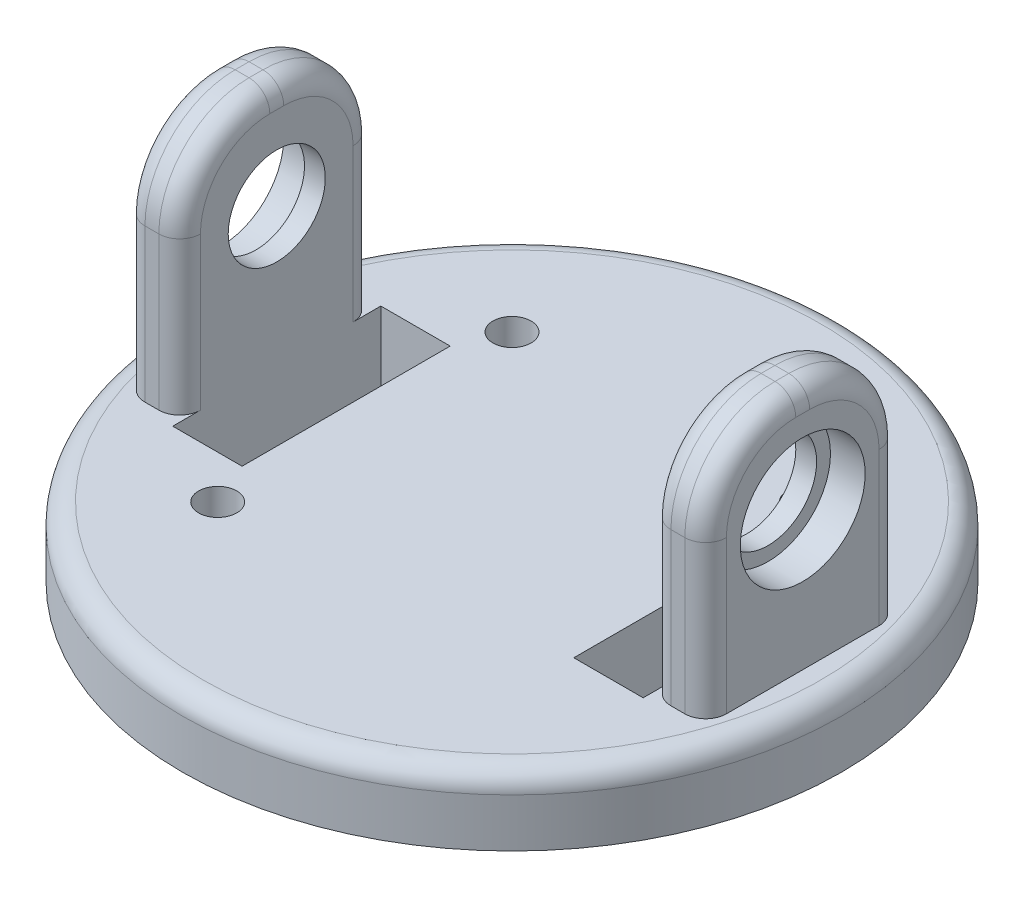
SolidWorks part; units mm, degrees
ref_plane "Front Plane" through (0, 0, 0) normal (0, 0, 1) x (1, 0, 0)
ref_plane "Top Plane" through (0, 0, 0) normal (0, 1, 0) x (1, 0, 0)
ref_plane "Right Plane" through (0, 0, 0) normal (1, 0, 0) x (0, 0, -1)
sketch "Sketch1" plane through (0, 0, 0) normal (0, 1, 0) x (1, 0, 0)
  circle A0 centre (0, 0) radius 47.5
  dimension "D1" = 95
extrude "Boss-Extrude1" add sketch "Sketch1" along normal blind 10
sketch "Sketch2" plane through (0, 10, 0) normal (0, 1, 0) x (1, 0, 0)
  line L0 (0, 0) -> (0, -17.7493) construction
  line L1 (-41.91, 14) -> (-33.91, 14)
  line L2 (-41.91, 14) -> (-41.91, -14)
  line L3 (-41.91, -14) -> (-33.91, -14)
  line L4 (-33.91, 14) -> (-33.91, -14)
  line L9 (33.91, 14) -> (33.91, -14)
  line L10 (41.91, -14) -> (33.91, -14)
  line L11 (41.91, 14) -> (41.91, -14)
  line L12 (41.91, 14) -> (33.91, 14)
  point P6 (-41.91, 0)
  dimension "D1" = 33.91
  dimension "D2" = 28
  dimension "D3" = 8
extrude "Boss-Extrude2" add sketch "Sketch2" along normal blind 35
sketch "Sketch3" plane through (0, 10, 0) normal (0, 1, 0) x (1, 0, 0)
  circle A0 centre (-21.2132, 21.2132) radius 2.75
  circle A1 centre (21.2132, 21.2132) radius 2.75
  circle A2 centre (-21.2132, -21.2132) radius 2.75
  circle A3 centre (0, 0) radius 30 construction
  point P9 (-17.284, 24.5207)
  point P10 (22.9527, 19.3177)
  point P11 (-15.6531, -25.5926)
  point P12 (-21.2448, 21.1816)
  point P13 (0, 0)
  dimension "D1" = 5.5
  dimension "D2" = 5.5
  dimension "D3" = 5.5
  dimension "D4" = 60
  dimension "D5" = 90
  dimension "D6" = 90
extrude "Cut-Extrude1" cut sketch "Sketch3" against normal blind 70
sketch "Sketch4" plane through (-41.91, 0, 0) normal (-1, 0, 0) x (0, 0, 1)
  line L0 (-14, 45) -> (14, 45) construction
  circle A0 centre (0, 30) radius 9
  dimension "D1" = 18
  dimension "D2" = 15
extrude "Cut-Extrude2" cut sketch "Sketch4" against normal blind 5
sketch "Sketch5" plane through (41.91, 0, 0) normal (1, 0, 0) x (0, 0, -1)
  line L0 (-14, 45) -> (14, 45) construction
  circle A0 centre (0, 30) radius 9
  dimension "D1" = 18
  dimension "D2" = 15
extrude "Cut-Extrude3" cut sketch "Sketch5" against normal blind 5
sketch "Sketch6" plane through (-36.91, 0, 0) normal (-1, 0, 0) x (0, 0, 1)
  circle A0 centre (0, 30) radius 7
  dimension "D1" = 14
extrude "Cut-Extrude4" cut sketch "Sketch6" against normal through all
fillet "Fillet1" radius 13 4 edges at (37.91, 45, 14) (37.91, 45, -14) (-37.91, 45, -14) (-37.91, 45, 14)
fillet "Fillet2" radius 3 20 edges at (41.91, 21, -14) (41.91, 41.1924, -10.1924) (41.91, 45, 0) (41.91, 41.1924, 10.1924) (33.91, 21, 14) (33.91, 41.1924, 10.1924) (33.91, 45, 0) (33.91, 41.1924, -10.1924) (-33.91, 21, -14) (-33.91, 41.1924, -10.1924) (-33.91, 45, 0) (-33.91, 41.1924, 10.1924) (-41.91, 21, -14) (-41.91, 41.1924, -10.1924) (-41.91, 45, 0) (-41.91, 41.1924, 10.1924) (41.91, 21, 14) (33.91, 21, -14) (-33.91, 21, 14) (-41.91, 21, 14)
fillet "Fillet3" radius 3 1 edges at (0, 10, 47.5)
sketch "Sketch7" plane through (0, 10, 0) normal (0, 1, 0) x (1, 0, 0)
  line L0 (-33.91, -11) -> (-33.91, 11) construction
  line L1 (-33.91, 15) -> (-23.91, 15)
  line L2 (-33.91, 15) -> (-33.91, -15)
  line L3 (-33.91, -15) -> (-23.91, -15)
  line L4 (-23.91, 15) -> (-23.91, -15)
  line L5 (0, 0) -> (0, 12.1381) construction
  line L6 (23.91, 15) -> (23.91, -15)
  line L7 (33.91, -15) -> (23.91, -15)
  line L8 (33.91, 15) -> (33.91, -15)
  line L9 (33.91, 15) -> (23.91, 15)
  point P7 (-23.91, 0)
  dimension "D1" = 30
  dimension "D2" = 10
extrude "Cut-Extrude5" cut sketch "Sketch7" against normal through all
